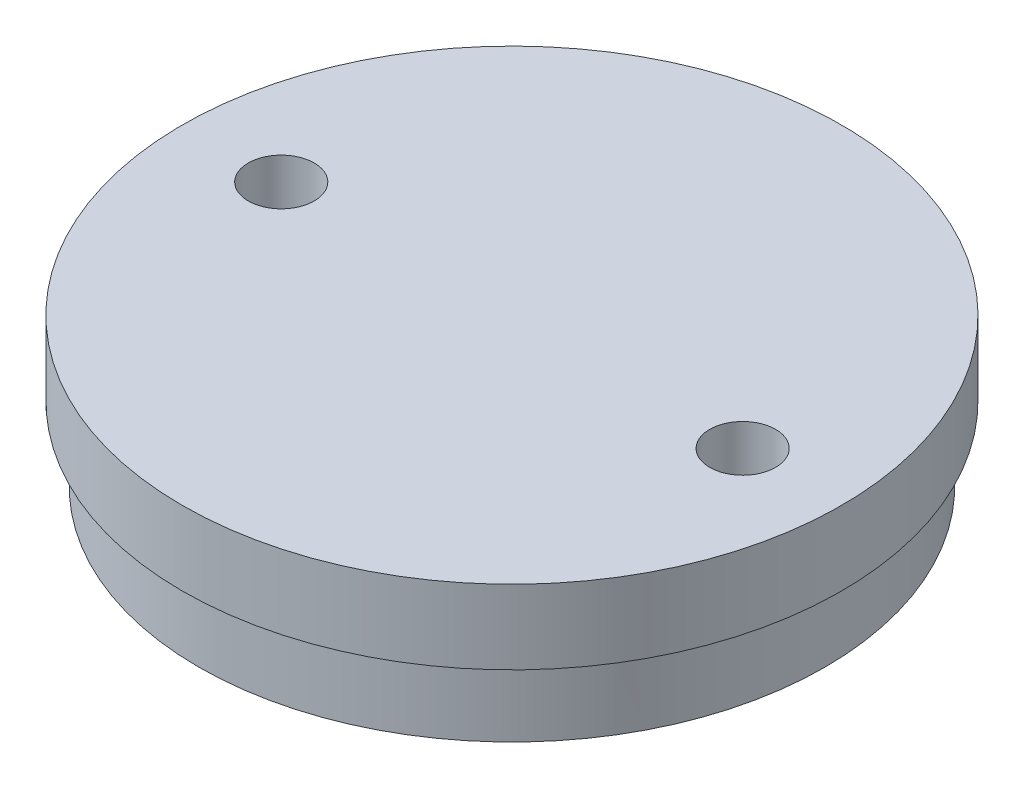
SolidWorks part; units mm, degrees
ref_plane "Front Plane" through (0, 0, 0) normal (0, 0, 1) x (1, 0, 0)
ref_plane "Top Plane" through (0, 0, 0) normal (0, 1, 0) x (1, 0, 0)
ref_plane "Right Plane" through (0, 0, 0) normal (1, 0, 0) x (0, 0, -1)
sketch "Sketch1" plane through (0, 0, 0) normal (0, 1, 0) x (1, 0, 0)
  circle A0 centre (0, 0) radius 40
  dimension "D1" = 80
extrude "Boss-Extrude1" add sketch "Sketch1" along normal blind 9
sketch "Sketch2" plane through (0, 0, 0) normal (0, -1, 0) x (1, 0, 0)
  circle A0 centre (0, 0) radius 38
  circle A1 centre (0, 0) radius 40 construction
  circle A2 centre (0, 0) radius 33
  dimension "D1" = 2
  dimension "D2" = 5
extrude "Boss-Extrude2" add sketch "Sketch2" along normal blind 9
hole_wizard "Ø8.0mm Dowel Hole1" positions "Sketch4" profile "Sketch6" hole size "Ø8.0" standard "ISO" end condition through all
sketch "Sketch4" plane through (0, 0, 0) normal (0, -1, 0) x (-1, 0, 0)
  line L0 (-28, 0) -> (0, 0)
  line L2 (0, 0) -> (28, 0)
  point P0 (-28, 0)
  point P2 (28, 0)
  dimension "D1" = 28
sketch "Sketch6" plane through (28, 0, 0) normal (1, 0, 0) x (0, 0, -1)
  line L0 (0, 0) -> (0, 9)
  line L1 (0, 9) -> (4, 9)
  line L2 (4, 9) -> (4, 0)
  line L5 (4, 0) -> (0, 0)
  line L11 (0, -6.35) -> (0, 107.95) construction
  dimension "Thru Hole Dia." = 8
  dimension "Thru Hole Depth" = 9
